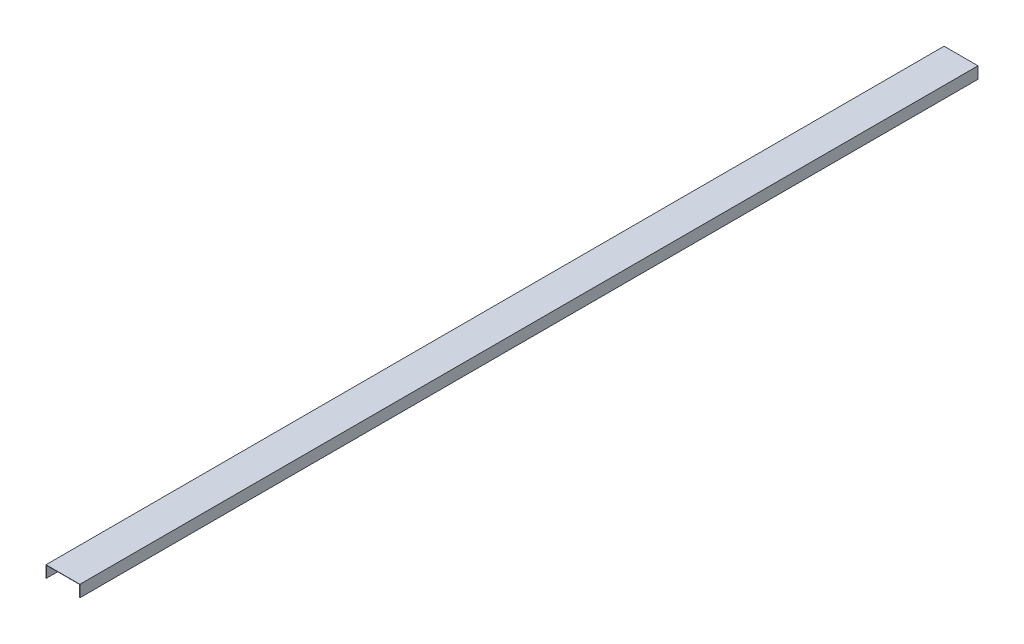
SolidWorks part; units mm, degrees
ref_plane "Front Plane" through (0, 0, 0) normal (0, 0, 1) x (1, 0, 0)
ref_plane "Top Plane" through (0, 0, 0) normal (0, 1, 0) x (1, 0, 0)
ref_plane "Right Plane" through (0, 0, 0) normal (1, 0, 0) x (0, 0, -1)
sketch "Sketch1" plane through (0, 0, 0) normal (0, 1, 0) x (1, 0, 0)
  line L1 (-46.0375, 1219.2) -> (46.0375, 1219.2)
  line L2 (-46.0375, 1219.2) -> (-46.0375, -1219.2)
  line L3 (-46.0375, -1219.2) -> (46.0375, -1219.2)
  line L4 (46.0375, 1219.2) -> (46.0375, -1219.2)
  line L5 (-46.0375, 1219.2) -> (46.0375, -1219.2) construction
  line L6 (-46.0375, -1219.2) -> (46.0375, 1219.2) construction
  point P0 (0, 0)
  dimension "D1" = 2438.4
  dimension "D2" = 92.075
extrude "Boss-Extrude1" add sketch "Sketch1" along normal blind 31.75
sketch "Sketch2" plane through (0, 0, 0) normal (0, 1, 0) x (1, 0, 0)
  line L0 (-46.0375, -1219.2) -> (46.0375, -1219.2) construction
  line L1 (-45.2755, 1219.2) -> (45.2755, 1219.2)
  line L2 (-45.2755, 1219.2) -> (-45.2755, -1219.2)
  line L3 (-45.2755, -1219.2) -> (45.2755, -1219.2)
  line L4 (45.2755, 1219.2) -> (45.2755, -1219.2)
  line L5 (-45.2755, 1219.2) -> (45.2755, -1219.2) construction
  line L6 (-45.2755, -1219.2) -> (45.2755, 1219.2) construction
  line L7 (46.0375, -1219.2) -> (46.0375, 1219.2) construction
  point P0 (0, 0)
  dimension "D1" = 0.762
extrude "Cut-Extrude1" cut sketch "Sketch2" along normal blind 30.988
